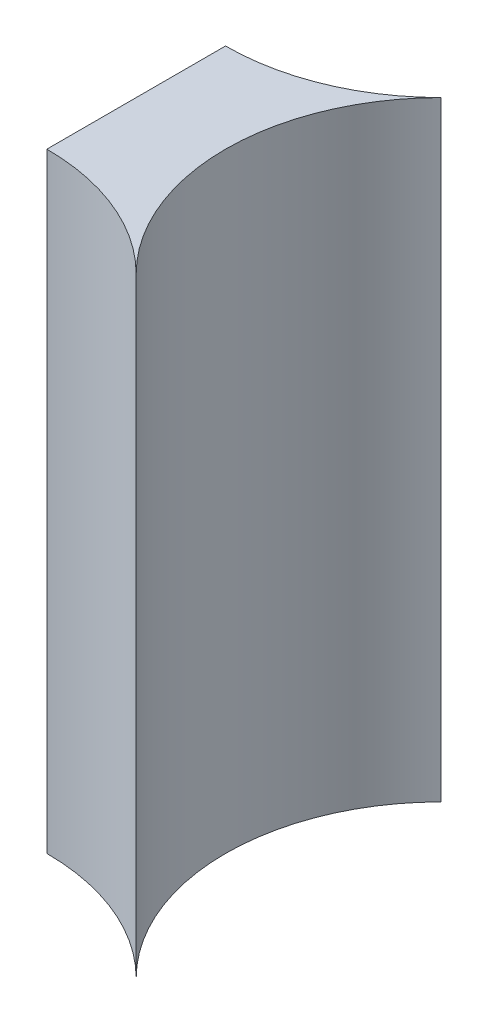
SolidWorks part; units mm, degrees
ref_plane "Front Plane" through (0, 0, 0) normal (0, 0, 1) x (1, 0, 0)
ref_plane "Top Plane" through (0, 0, 0) normal (0, 1, 0) x (1, 0, 0)
ref_plane "Right Plane" through (0, 0, 0) normal (1, 0, 0) x (0, 0, -1)
sketch "Sketch1" plane through (0, 0, 0) normal (0, 1, 0) x (1, 0, 0)
  line L0 (0, 1.4645) -> (0, -1.4645)
  line L5 (-2.5, -2.5) -> (2.5, 2.5) construction
  line L6 (-2.5, 2.5) -> (2.5, -2.5) construction
  circle A2 centre (0, 0) radius 3.5355 construction
  arc A5 (0, 1.4645) -> (2.5, 2.5) centre (0, 5) ccw
  arc A6 (2.5, 2.5) -> (2.5, -2.5) centre (5, 0) ccw
  arc A7 (0, -1.4645) -> (2.5, -2.5) centre (0, -5) cw
  point P0 (0, 0)
  dimension "D1" = 5
  dimension "D2" = 5
  dimension "D4" = 3.5355
extrude "Boss-Extrude1" add sketch "Sketch1" along normal blind 10 contours A6 A7 L0 A5
